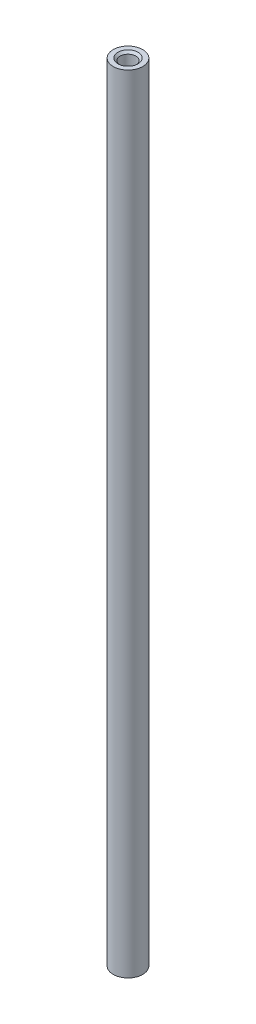
SolidWorks part; units mm, degrees
ref_plane "Front Plane" through (0, 0, 0) normal (0, 0, 1) x (1, 0, 0)
ref_plane "Top Plane" through (0, 0, 0) normal (0, 1, 0) x (1, 0, 0)
ref_plane "Right Plane" through (0, 0, 0) normal (1, 0, 0) x (0, 0, -1)
sketch "Sketch1" plane through (0, 0, 0) normal (0, 1, 0) x (1, 0, 0)
  circle A0 centre (0, 0) radius 1.5
  dimension "D1" = 3
extrude "Boss-Extrude1" add sketch "Sketch1" along normal blind 80
sketch "Sketch2" plane through (0, 80, 0) normal (0, 1, 0) x (1, 0, 0)
  circle A0 centre (0, 0) radius 1
hole_wizard "M2 Tapped Hole1" positions "Sketch3" profile "Sketch4" tap size "M2" standard "ISO"
sketch "Sketch3" plane through (0, 80, 0) normal (0, 1, 0) x (1, 0, 0)
  point P0 (0, 0)
sketch "Sketch4" plane through (0, 80, 0) normal (1, 0, 0) x (0, 0, 1)
  line L0 (0, 0) -> (0, 8.4807)
  line L1 (0, 8.4807) -> (0.8, 8)
  line L2 (0.8, 8) -> (0.8, 0.225)
  line L3 (0.8, 0.225) -> (1.025, 0)
  line L5 (1.025, 0) -> (0, 0)
  line L6 (-0.8, 0.225) -> (-1.025, 0) construction
  line L10 (0, 8.4807) -> (-0.8, 8) construction
  line L11 (0, -6.35) -> (0, 107.95) construction
  dimension "Tap Drill Dia." = 1.6
  dimension "Tap Drill Depth" = 8
  dimension "Near C'Sink Dia." = 2.05
  dimension "Near C'Sink Angle" = 90
  dimension "Drill Angle" = 118
cosmetic thread "Hole Thread1"
sketch "Sketch5" plane through (0, 0, 0) normal (0, -1, 0) x (1, 0, 0)
  circle A0 centre (0, 0) radius 1
hole_wizard "M2 Tapped Hole2" positions "Sketch6" profile "Sketch7" tap size "M2" standard "ISO"
sketch "Sketch6" plane through (0, 0, 0) normal (0, -1, 0) x (-1, 0, 0)
  point P0 (0, 0)
sketch "Sketch7" plane through (0, 0, 0) normal (1, 0, 0) x (0, 0, -1)
  line L0 (0, 0) -> (0, 8.4807)
  line L1 (0, 8.4807) -> (0.8, 8)
  line L2 (0.8, 8) -> (0.8, 0.225)
  line L3 (0.8, 0.225) -> (1.025, 0)
  line L5 (1.025, 0) -> (0, 0)
  line L6 (-0.8, 0.225) -> (-1.025, 0) construction
  line L10 (0, 8.4807) -> (-0.8, 8) construction
  line L11 (0, -6.35) -> (0, 107.95) construction
  dimension "Tap Drill Dia." = 1.6
  dimension "Tap Drill Depth" = 8
  dimension "Near C'Sink Dia." = 2.05
  dimension "Near C'Sink Angle" = 90
  dimension "Drill Angle" = 118
cosmetic thread "Hole Thread2"
